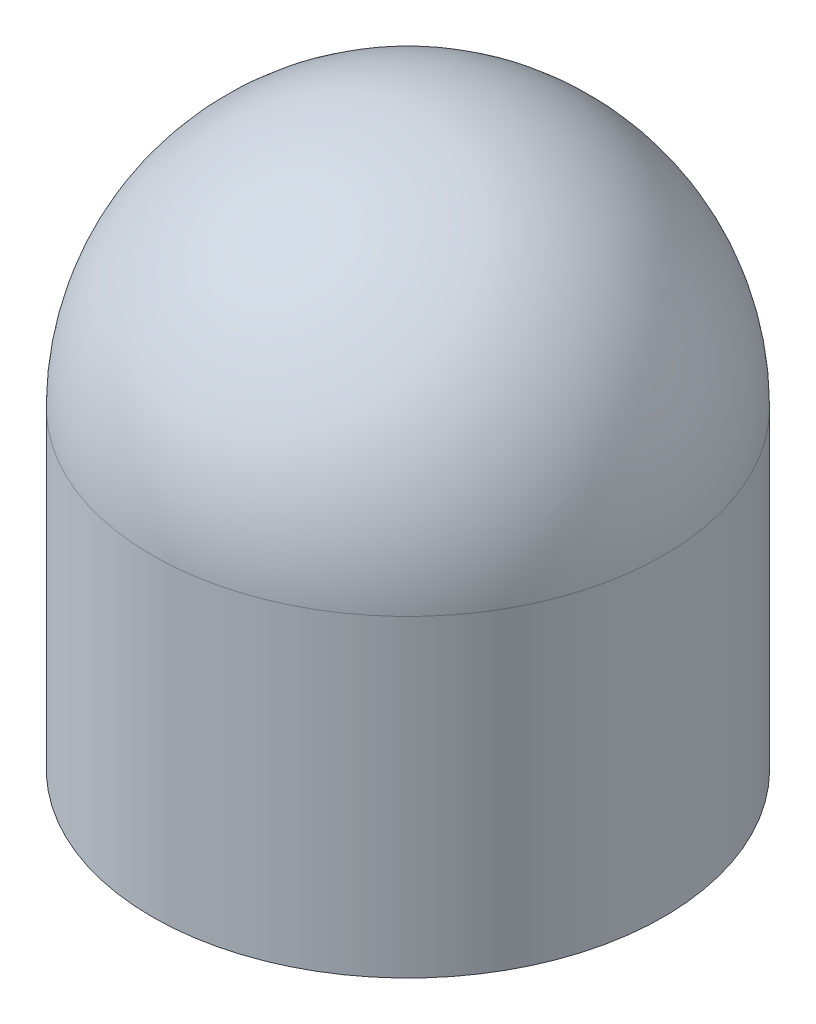
SolidWorks part; units mm, degrees
material "PBT General Purpose"
ref_plane "Front Plane" through (0, 0, 0) normal (0, 0, 1) x (1, 0, 0)
ref_plane "Top Plane" through (0, 0, 0) normal (0, 1, 0) x (1, 0, 0)
ref_plane "Right Plane" through (0, 0, 0) normal (1, 0, 0) x (0, 0, -1)
sketch "Sketch2" plane through (0, 0, 0) normal (0, 1, 0) x (1, 0, 0)
  circle A0 centre (0, 0) radius 24.5
  dimension "D1" = 49
extrude "Boss-Extrude1" add sketch "Sketch2" along normal blind 30
sketch "Sketch4" plane through (0, 30, 0) normal (0, 1, 0) x (1, 0, 0)
  arc A1 (24.5, 0) -> (-24.5, 0) centre (0, 0) cw
  circle A2 centre (0, 0) radius 24.5 construction
sketch "Sketch5" plane through (0, 30, 0) normal (0, 1, 0) x (1, 0, 0)
  line L0 (0, 0) -> (17.3309, 0)
  point P3 (17.3309, 0)
revolve "Revolve-Thin1" add sketch "Sketch4" angle 180 about L0
sketch "Sketch6" plane through (0, 0, 0) normal (0, -1, 0) x (1, 0, 0)
  circle A0 centre (0, 0) radius 22.9
  circle A1 centre (0, 0) radius 24.5 construction
  dimension "D1" = 1.6
extrude "Cut-Extrude1" cut sketch "Sketch6" against normal blind 30
